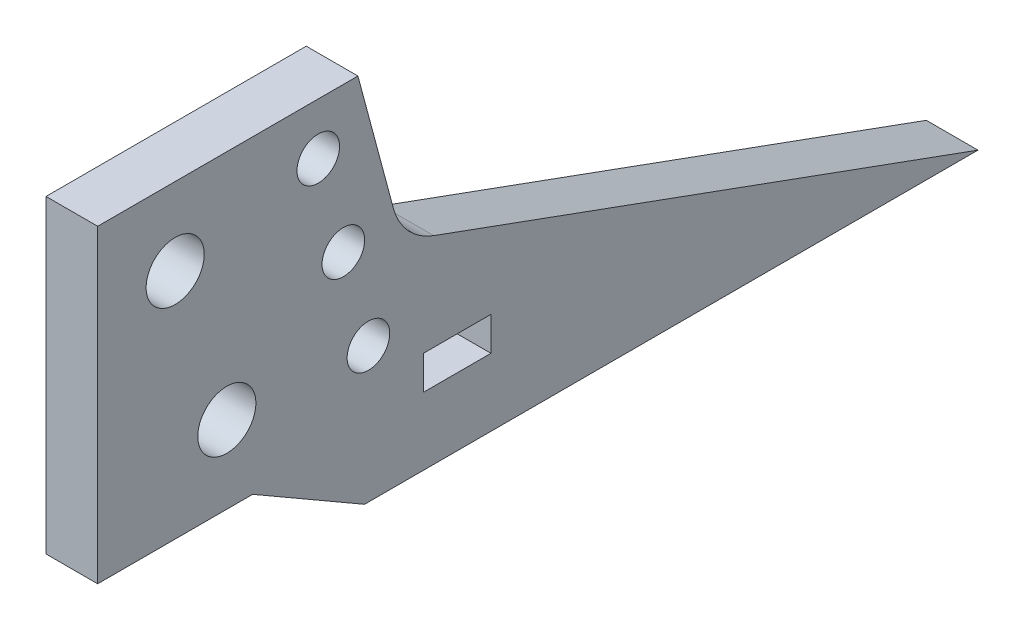
SolidWorks part; units mm, degrees
material "AISI 4340 Aço recozido"
ref_plane "Plano frontal" through (0, 0, 0) normal (0, 0, 1) x (1, 0, 0)
ref_plane "Plano superior" through (0, 0, 0) normal (0, 1, 0) x (1, 0, 0)
ref_plane "Plano direito" through (0, 0, 0) normal (1, 0, 0) x (0, 0, -1)
sketch "Esboço1" plane through (0, 0, 0) normal (1, 0, 0) x (0, 0, -1)
  line L1 (28, 74) -> (39.1299, 32.4627)
  line L3 (33.3205, 0) -> (128.3205, 0)
  line L4 (28, 74) -> (0, 74)
  line L8 (128.3205, 0) -> (39.1299, 32.4627)
  line L10 (16, 10) -> (0, 10)
  line L11 (0, 10) -> (0, 74)
  line L12 (39.1299, 32.4627) -> (0, 32.4627) construction
  line L15 (33.3205, 0) -> (16, 10)
  dimension "D1" = 10
  dimension "D2" = 210
  dimension "D3" = 20
  dimension "D4" = 16
  dimension "D5" = 64
  dimension "D6" = 75
  dimension "D7" = 28
  dimension "D8" = 95
extrude "Ressalto-extrusão1" add sketch "Esboço1" along normal blind 8
sketch "Esboço2" plane through (8, 0, 0) normal (1, 0, 0) x (0, 0, -1)
  line L0 (39.1299, 32.4627) -> (28, 74) construction
  line L1 (0, 74) -> (32.3, 74)
  line L2 (0, 74) -> (0, 57.9522)
  line L3 (0, 57.9522) -> (32.3, 57.9522)
  line L4 (32.3, 74) -> (32.3, 57.9522)
  dimension "D1" = 32.3
extrude "Corte-extrusão1" cut sketch "Esboço2" against normal through all
sketch "Esboço3" plane through (8, 0, 0) normal (1, 0, 0) x (0, 0, -1)
  line L0 (0, 10) -> (16, 10) construction
  line L1 (0, 57.9522) -> (-8, 57.9522)
  line L2 (0, 57.9522) -> (0, 10)
  line L3 (0, 10) -> (-8, 10)
  line L4 (-8, 57.9522) -> (-8, 10)
  dimension "D1" = 8
extrude "Ressalto-extrusão2" add sketch "Esboço3" against normal up to surface (8 mm away) up to face at (0, 24.0524, -35.5816)
hole_wizard "Furo com folga de M81" positions "Esboço4" profile "Esboço5" hole size "M8" standard "ISO" end condition through all
sketch "Esboço4" plane through (0, 0, 0) normal (-1, 0, 0) x (0, 0, 1)
  line L0 (8, 57.9522) -> (8, 10) construction
  line L1 (8, 57.9522) -> (-32.3, 57.9522) construction
  line L2 (8, 10) -> (-16, 10) construction
  point P1 (-4, 45.9522)
  point P3 (-12, 22)
  dimension "D1" = 12
  dimension "D2" = 12
  dimension "D3" = 12
  dimension "D4" = 4
sketch "Esboço5" plane through (0, 45.9522, -4) normal (0, 1, 0) x (0, 0, 1)
  line L0 (0, 0) -> (0, 8)
  line L1 (0, 8) -> (4.5, 8)
  line L2 (4.5, 8) -> (4.5, 0)
  line L5 (4.5, 0) -> (0, 0)
  line L11 (0, -6.35) -> (0, 107.95) construction
  dimension "Thru Hole Dia." = 9
  dimension "Thru Hole Depth" = 8
hole_wizard "Furo com folga de M61" positions "Esboço6" profile "Esboço7" hole size "M6" standard "ISO" end condition through all
sketch "Esboço6" plane through (8, 0, 0) normal (1, 0, 0) x (0, 0, -1)
  line L0 (26.1614, 49.9522) -> (33.926, 20.9744) construction
  line L3 (-8, 57.9522) -> (-8, 10) construction
  line L6 (39.1299, 32.4627) -> (32.3, 57.9522) construction
  line L7 (-8, 57.9522) -> (32.3, 57.9522) construction
  point P0 (26.1614, 49.9522)
  point P2 (30.0437, 35.4633)
  point P4 (33.926, 20.9744)
  dimension "D1" = 8
  dimension "D2" = 15
  dimension "D3" = 15
  dimension "D4" = 30
  dimension "D5" = 8
sketch "Esboço7" plane through (8, 49.9522, -26.1614) normal (0, 1, 0) x (0, 0, -1)
  line L0 (0, 0) -> (0, 8)
  line L1 (0, 8) -> (3.3, 8)
  line L2 (3.3, 8) -> (3.3, 0)
  line L5 (3.3, 0) -> (0, 0)
  line L11 (0, -6.35) -> (0, 107.95) construction
  dimension "Thru Hole Dia." = 6.6
  dimension "Thru Hole Depth" = 8
sketch "Esboço8" plane through (8, 0, 0) normal (1, 0, 0) x (0, 0, -1)
  line L0 (128.3205, 0) -> (68.3205, 0)
  line L1 (33.3205, 0) -> (128.3205, 0) construction
  line L2 (68.3205, 0) -> (68.3205, -2.0952)
  line L3 (68.3205, -2.0952) -> (128.3205, 0)
  dimension "D1" = 60
  dimension "D2" = 2
extrude "Ressalto-extrusão3" [suppressed] add sketch "Esboço8" against normal blind 8
fillet "Filete1" radius 10 1 edges at (4, 32.4627, -39.1299)
fillet "Filete2" [suppressed] radius 10
sketch "Esboço9" plane through (8, 0, 0) normal (1, 0, 0) x (0, 0, -1)
  line L1 (42.4466, 10.4639) -> (52.9006, 10.4639)
  line L2 (42.4466, 10.4639) -> (42.4466, 15.6909)
  line L3 (42.4466, 15.6909) -> (52.9006, 15.6909)
  line L4 (52.9006, 10.4639) -> (52.9006, 15.6909)
extrude "Corte-extrusão2" cut sketch "Esboço9" against normal through all
